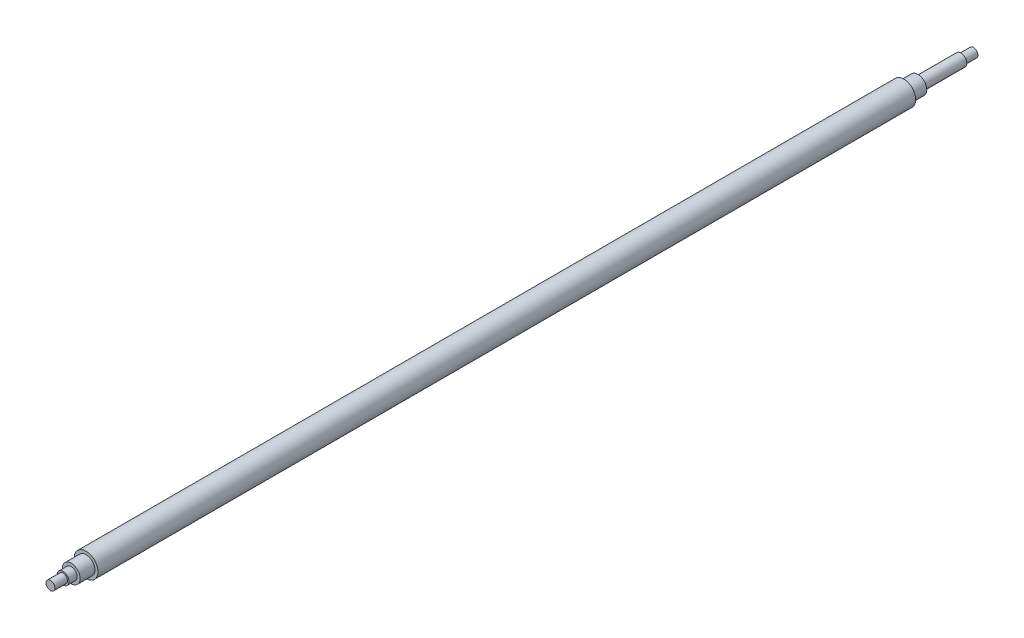
SolidWorks part; units mm, degrees
ref_plane "Piano frontale" through (0, 0, 0) normal (0, 0, 1) x (1, 0, 0)
ref_plane "Piano superiore" through (0, 0, 0) normal (0, 1, 0) x (1, 0, 0)
ref_plane "Piano destro" through (0, 0, 0) normal (1, 0, 0) x (0, 0, -1)
sketch "Schizzo2" plane through (0, 0, 0) normal (1, 0, 0) x (0, 0, -1)
  line L0 (0, 0) -> (0, 3)
  line L1 (0, 3) -> (8.5, 3)
  line L2 (8.5, 3) -> (8.5, 4)
  line L3 (8.5, 4) -> (14, 4)
  line L4 (14, 4) -> (14, 6)
  line L5 (14, 6) -> (24, 6)
  line L6 (24, 6) -> (24, 8)
  line L7 (24, 8) -> (575, 8)
  line L8 (575, 8) -> (575, 6)
  line L9 (575, 6) -> (584.5, 6)
  line L10 (584.5, 6) -> (584.5, 4)
  line L11 (622, 0) -> (0, 0)
  line L14 (622, 0) -> (622, 3)
  line L15 (0, 0) -> (351.0218, 0) construction
  line L16 (613.5, 3) -> (622, 3)
  line L17 (613.5, 4) -> (613.5, 3)
  line L18 (584.5, 4) -> (613.5, 4)
  point P33 (0, 0)
  dimension "D2" = 6
  dimension "D3" = 8
  dimension "D4" = 12
  dimension "D5" = 16
  dimension "D6" = 12
  dimension "D7" = 8
  dimension "D8" = 8.5
  dimension "D9" = 5.5
  dimension "D10" = 10
  dimension "D11" = 551
  dimension "D12" = 9.5
  dimension "D13" = 29
  dimension "D14" = 8.5
  dimension "D15" = 6
revolve "Rivoluzione2" add sketch "Schizzo2" angle 360 about L15
